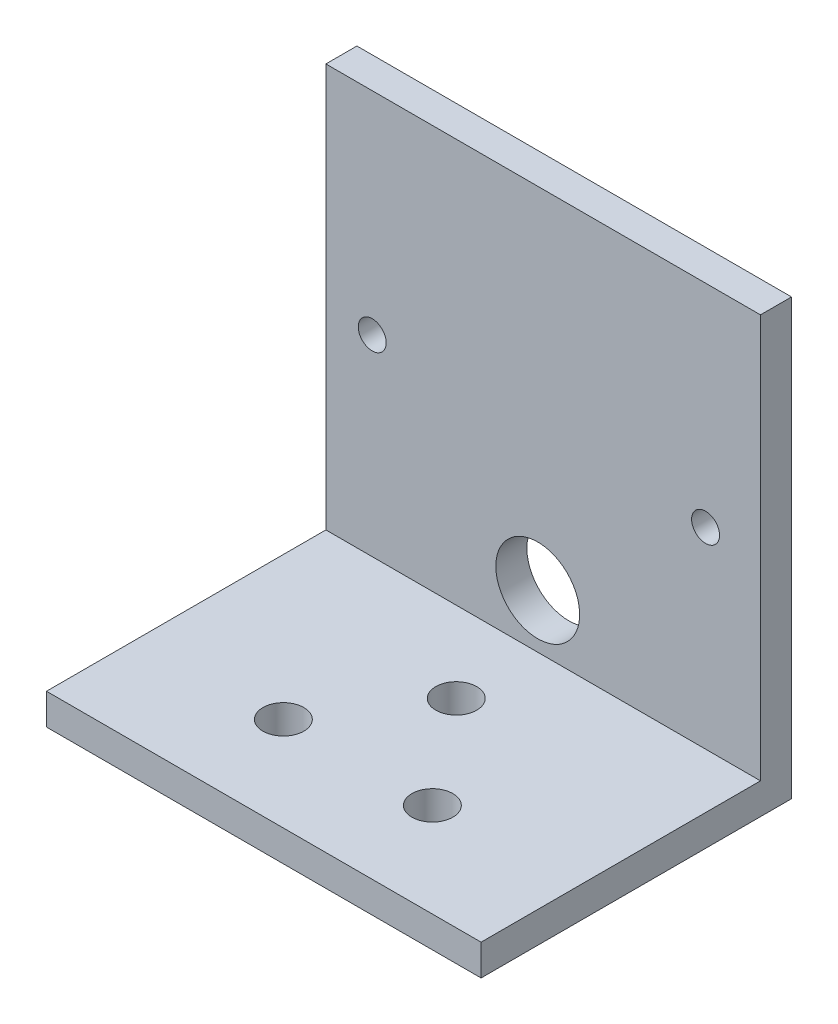
SolidWorks part; units mm, degrees
ref_plane "Plan de face" through (0, 0, 0) normal (0, 0, 1) x (1, 0, 0)
ref_plane "Plan de dessus" through (0, 0, 0) normal (0, 1, 0) x (1, 0, 0)
ref_plane "Plan de droite" through (0, 0, 0) normal (1, 0, 0) x (0, 0, -1)
sketch "Esquisse1" plane through (0, 0, 0) normal (0, 0, 1) x (1, 0, 0)
  line L1 (-35, -35) -> (35, -35)
  line L2 (-35, -35) -> (-35, 35)
  line L3 (-35, 35) -> (35, 35)
  line L4 (35, -35) -> (35, 35)
  line L5 (-35, -35) -> (35, 35) construction
  line L6 (-35, 35) -> (35, -35) construction
  point P0 (0, 0)
  dimension "D1" = 70
  dimension "D2" = 70
extrude "Boss.-Extru.1" add sketch "Esquisse1" along normal blind 50
sketch "Esquisse2" plane through (35, 0, 0) normal (1, 0, 0) x (0, 0, -1)
  line L8 (-5, -30) -> (-5, 30)
  line L9 (-5, 30) -> (-45, 30)
  line L10 (-45, 30) -> (-45, -30)
  line L11 (-45, -30) -> (-5, -30)
  line L12 (-5, -30) -> (-5, 56.8641)
  line L13 (-5, 56.8641) -> (-128.1376, 56.8641)
  line L14 (-128.1376, 56.8641) -> (-128.1376, -30)
  line L15 (-128.1376, -30) -> (-5, -30)
  dimension "D1" = 5
extrude "Enlèv. mat.-Extru.1" cut sketch "Esquisse2" against normal blind 217
hole_wizard "Dégagement M41" positions "Esquisse4" profile "Esquisse3" hole size "M4" standard "JIS" end condition through all
sketch "Esquisse4" plane through (0, 0, 0) normal (0, 0, -1) x (-1, 0, 0)
  point P0 (-26.1576, 0.9464)
  point P2 (27.5331, 0.9464)
sketch "Esquisse3" plane through (26.1576, 0.9464, 0) normal (1, 0, 0) x (0, 1, 0)
  line L0 (0, 0) -> (0, 50)
  line L1 (0, 50) -> (2.25, 50)
  line L2 (2.25, 50) -> (2.25, 0)
  line L5 (2.25, 0) -> (0, 0)
  line L11 (0, -6.35) -> (0, 107.95) construction
  dimension "Diamètre du perçage jusqu'au prochain" = 4.5
  dimension "Profondeur du perçage jusqu'au prochain" = 50
hole_wizard "Dégagement M121" positions "Esquisse6" profile "Esquisse5" hole size "M12" standard "JIS" end condition through all
sketch "Esquisse6" plane through (0, 0, 0) normal (0, 0, -1) x (-1, 0, 0)
  point P0 (0.8755, -21.3664)
sketch "Esquisse5" plane through (-0.8755, -21.3664, 0) normal (1, 0, 0) x (0, 1, 0)
  line L0 (0, 0) -> (0, 50)
  line L1 (0, 50) -> (6.75, 50)
  line L2 (6.75, 50) -> (6.75, 0)
  line L5 (6.75, 0) -> (0, 0)
  line L11 (0, -6.35) -> (0, 107.95) construction
  dimension "Diamètre du perçage jusqu'au prochain" = 13.5
  dimension "Profondeur du perçage jusqu'au prochain" = 50
hole_wizard "M6 Clearance Hole1" positions "Sketch2" profile "Sketch1" hole size "M6" standard "ANSI Metric" end condition through all
sketch "Sketch2" plane through (0, -30, 0) normal (0, 1, 0) x (1, 0, 0)
  line L0 (35, -50) -> (35, -5) construction
  line L1 (-35, -50) -> (-35, -5) construction
  line L2 (35, -50) -> (-35, -50) construction
  point P0 (-12, -34.8456)
  point P2 (12, -34.8456)
  point P4 (-1, -18)
  dimension "D1" = 23
  dimension "D2" = 23
  dimension "D3" = 32
  dimension "D4" = 36
sketch "Sketch1" plane through (-12, -30, 34.8456) normal (1, 0, 0) x (0, 0, 1)
  line L0 (0, 0) -> (0, 5)
  line L1 (0, 5) -> (3.3, 5)
  line L2 (3.3, 5) -> (3.3, 0)
  line L5 (3.3, 0) -> (0, 0)
  line L11 (0, -6.35) -> (0, 107.95) construction
  dimension "Thru Hole Dia." = 6.6
  dimension "Thru Hole Depth" = 5
